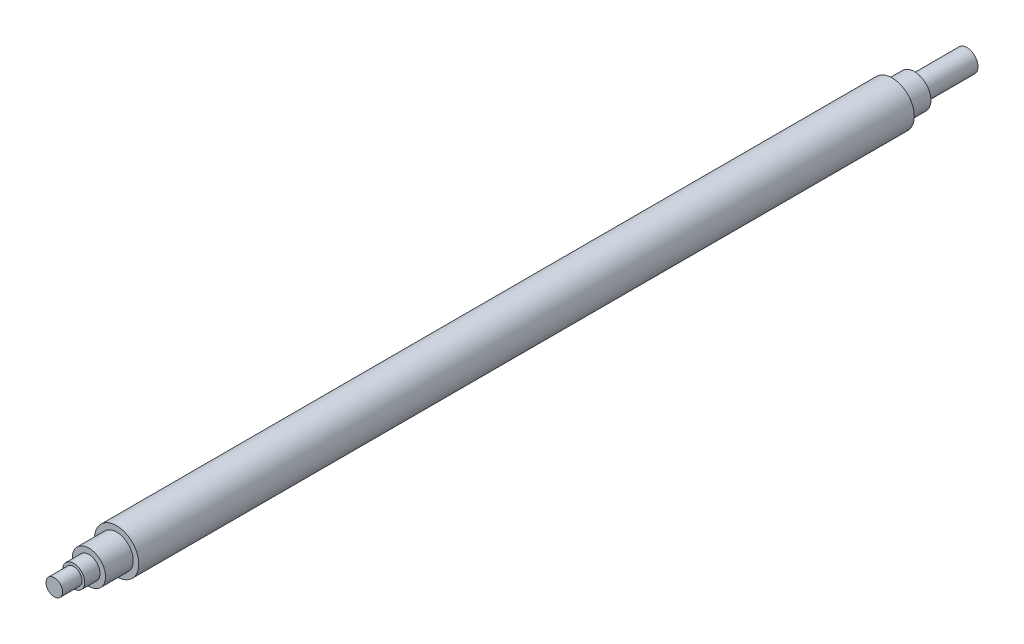
SolidWorks part; units mm, degrees
ref_plane "Piano frontale" through (0, 0, 0) normal (0, 0, 1) x (1, 0, 0)
ref_plane "Piano superiore" through (0, 0, 0) normal (0, 1, 0) x (1, 0, 0)
ref_plane "Piano destro" through (0, 0, 0) normal (1, 0, 0) x (0, 0, -1)
sketch "Schizzo2" plane through (0, 0, 0) normal (1, 0, 0) x (0, 0, -1)
  line L0 (1.5, 0) -> (1.5, 3)
  line L1 (1.5, 3) -> (8.5, 3)
  line L2 (8.5, 3) -> (8.5, 4)
  line L3 (8.5, 4) -> (14, 4)
  line L4 (14, 4) -> (14, 6)
  line L5 (14, 6) -> (24, 6)
  line L6 (24, 6) -> (24, 8)
  line L7 (24, 8) -> (304, 8)
  line L8 (304, 8) -> (304, 6)
  line L9 (304, 6) -> (312, 6)
  line L10 (312, 6) -> (312, 4)
  line L11 (331, 0) -> (1.5, 0)
  line L14 (331, 0) -> (331, 4)
  line L15 (0, 0) -> (351.0218, 0) construction
  line L18 (312, 4) -> (331, 4)
  point P33 (0, 0)
  dimension "D2" = 6
  dimension "D3" = 8
  dimension "D4" = 12
  dimension "D5" = 16
  dimension "D6" = 12
  dimension "D7" = 8
  dimension "D8" = 7
  dimension "D9" = 5.5
  dimension "D10" = 10
  dimension "D11" = 280
  dimension "D12" = 8
  dimension "D13" = 19
revolve "Rivoluzione2" add sketch "Schizzo2" angle 360 about L15
